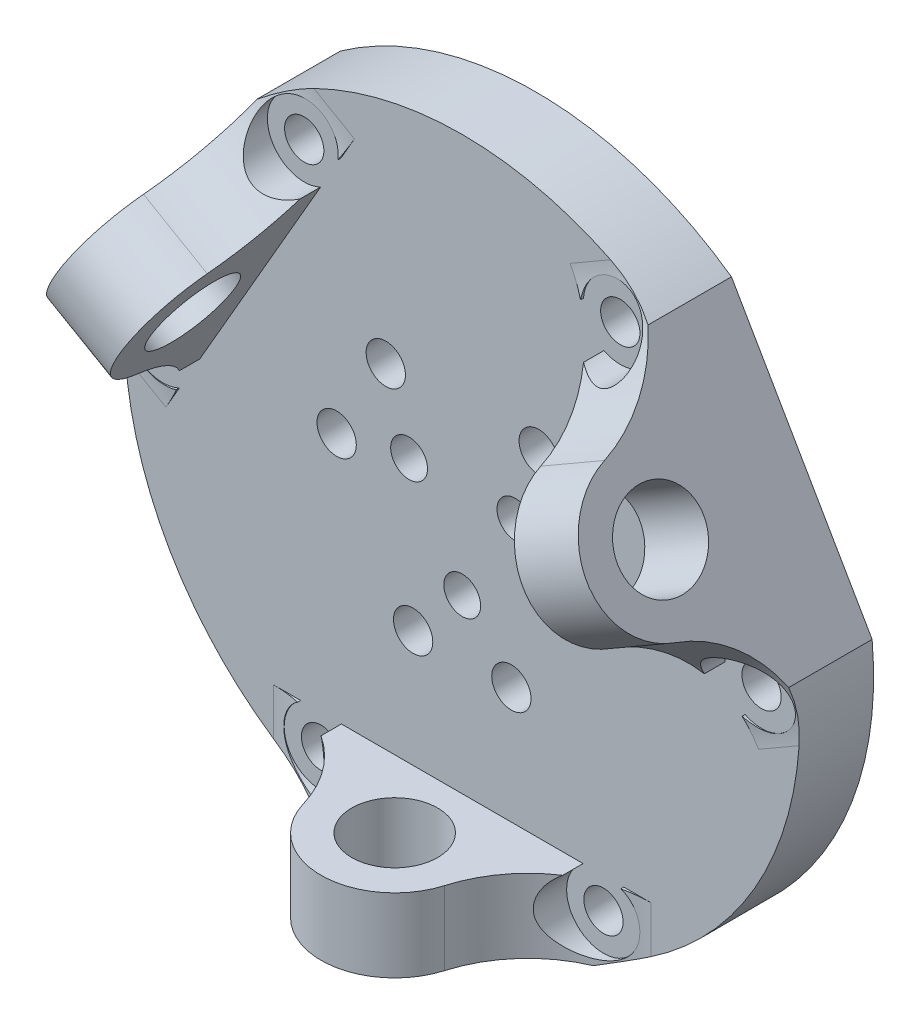
SolidWorks part; units mm, degrees
material "ABS"
ref_plane "前视基准面" through (0, 0, 0) normal (0, 0, 1) x (1, 0, 0)
ref_plane "上视基准面" through (0, 0, 0) normal (0, 1, 0) x (1, 0, 0)
ref_plane "右视基准面" through (0, 0, 0) normal (1, 0, 0) x (0, 0, -1)
sketch "草图1" plane through (0, 0, 0) normal (0, 0, 1) x (1, 0, 0)
  circle A1 centre (0, 25) radius 27.5
  dimension "D1" = 55
  dimension "D2" = 25
extrude "凸台-拉伸1" add sketch "草图1" along normal blind 6
sketch "草图2" plane through (0, 0, 0) normal (0, 1, 0) x (1, 0, 0)
  circle A0 centre (0, -11.5) radius 6
  circle A1 centre (0, -11.5) radius 3.5
  dimension "D1" = 12
  dimension "D2" = 7
  dimension "D3" = 11.5
extrude "凸台-拉伸2" add sketch "草图2" along normal blind 6
pattern_circular "阵列(圆周)3" count 3 over 360 about axis through (0, 25, 0) along (0, 0, 1) of "凸台-拉伸2"
sketch "草图5" plane through (0, 0, 6) normal (0, 0, 1) x (1, 0, 0)
  line L0 (-15.9224, 47.4216) -> (-27.3789, 27.5784)
  line L1 (15.9224, 47.4216) -> (27.3789, 27.5784)
  line L2 (11.4564, 0) -> (-11.4564, 0)
  line L3 (-18.6506, 42.6962) -> (-24.6506, 32.3038) construction
  line L4 (24.6506, 32.3038) -> (18.6506, 42.6962) construction
  line L5 (-6, 0) -> (6, 0) construction
  circle A0 centre (0, 25) radius 27.5 construction
  circle M4 centre (0, 25) radius 27.5
  line M5 (2.3979, 0) -> (-2.3979, 0)
  line M9 (20.4517, 39.5767) -> (22.8496, 35.4233)
  line M13 (-22.8496, 35.4233) -> (-20.4517, 39.5767)
extrude "切除-拉伸1" cut sketch "草图5" against normal through all contours L0 M4 M13 | L2 M4 M5 | L1 M4 M9
fillet "圆角1" radius 10 6 edges at (-17.8536, 38.0767, 6) (-20.2515, 33.9233, 6) (20.2515, 33.9233, 6) (17.8536, 38.0767, 6) (-2.3979, 3, 6) (2.3979, 3, 6)
sketch "草图6" plane through (0, 0, 0) normal (0, 0, -1) x (-1, 0, 0)
  line L0 (-11.4564, 0) -> (11.4564, 0) construction
  circle A0 centre (-11.5, 3.5) radius 1.6
  circle A1 centre (11.5, 3.5) radius 1.6
  circle A2 centre (-4, 15.5) radius 1.6
  circle A3 centre (4, 15.5) radius 1.6
  dimension "D1" = 23
  dimension "D2" = 3.5
  dimension "D3" = 3.5
  dimension "D4" = 3.2
  dimension "D5" = 3.2
  dimension "D6" = 11.5
  dimension "D7" = 8
  dimension "D8" = 4
  dimension "D9" = 12
  dimension "D10" = 12
  dimension "D11" = 3.2
  dimension "D12" = 3.2
extrude "切除-拉伸2" cut sketch "草图6" against normal through all
sketch "草图7" plane through (0, 0, 6) normal (0, 0, 1) x (1, 0, 0)
  circle A0 centre (-11.5, 3.5) radius 3
  circle A1 centre (11.5, 3.5) radius 3
  dimension "D1" = 6
  dimension "D2" = 6
extrude "切除-拉伸3" cut sketch "草图7" along normal through all
pattern_circular "阵列(圆周)4" count 3 over 360 about axis through (0, 25, 0) along (0, 0, 1) of "切除-拉伸3", "切除-拉伸2"
sketch "草图8" plane through (0, 0, 6) normal (0, 0, 1) x (1, 0, 0)
  circle A0 centre (0, 20) radius 1.5
  circle A1 centre (-4.3301, 27.5) radius 1.5
  circle A2 centre (4.3301, 27.5) radius 1.5
  arc A3 (-27.435, 23.1101) -> (-15.3542, 2.1855) centre (0, 25) ccw construction
  point P9 (0, 25)
  dimension "D1" = 3
  dimension "D2" = 20
  dimension "D3" = 3
extrude "切除-拉伸4" cut sketch "草图8" against normal through all
fillet "圆角2" radius 1 3 edges at (1.5, 20, 0) (-2.8301, 27.5, 0) (5.8301, 27.5, 0)
